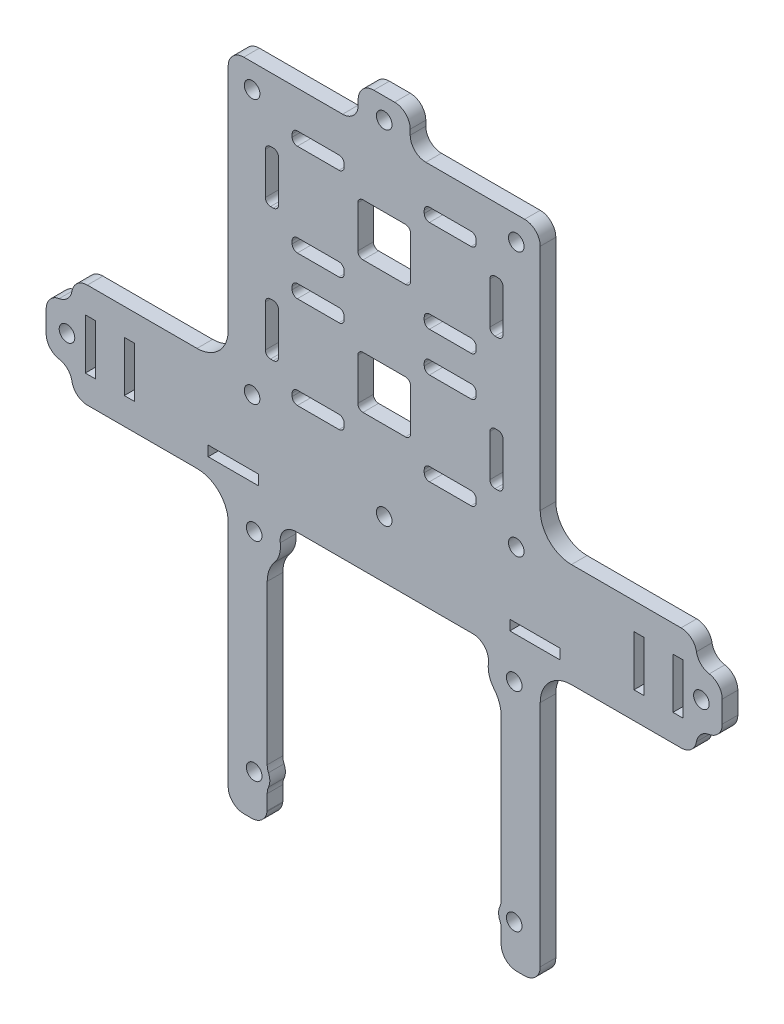
SolidWorks part; units mm, degrees
ref_plane "Спереди" through (0, 0, 0) normal (0, 0, 1) x (1, 0, 0)
ref_plane "Сверху" through (0, 0, 0) normal (0, 1, 0) x (1, 0, 0)
ref_plane "Справа" through (0, 0, 0) normal (1, 0, 0) x (0, 0, -1)
sketch "Model" plane through (0, 0, 0) normal (0, 0, 1) x (1, 0, 0)
  line L0 (5.08, 16.3) -> (5.08, 24.3)
  line L1 (4.08, 25.3) -> (-4.08, 25.3)
  line L2 (-5.08, 24.3) -> (-5.08, 16.3)
  line L3 (-4.08, 15.3) -> (4.08, 15.3)
  line L4 (5.08, 41.7) -> (5.08, 49.7)
  line L5 (4.08, 50.7) -> (-4.08, 50.7)
  line L6 (-5.08, 49.7) -> (-5.08, 41.7)
  line L7 (-4.08, 40.7) -> (4.08, 40.7)
  line L8 (16.7, 55.86) -> (8.7, 55.86)
  line L9 (7.7, 54.86) -> (7.7, 54.32)
  line L10 (8.7, 53.32) -> (16.7, 53.32)
  line L11 (17.7, 54.32) -> (17.7, 54.86)
  line L12 (22.86, 41.7) -> (22.86, 49.7)
  line L13 (21.86, 50.7) -> (21.32, 50.7)
  line L14 (20.32, 49.7) -> (20.32, 41.7)
  line L15 (21.32, 40.7) -> (21.86, 40.7)
  line L16 (22.86, 16.3) -> (22.86, 24.3)
  line L17 (21.86, 25.3) -> (21.32, 25.3)
  line L18 (20.32, 24.3) -> (20.32, 16.3)
  line L19 (21.32, 15.3) -> (21.86, 15.3)
  line L20 (8.7, 10.14) -> (16.7, 10.14)
  line L21 (17.7, 11.14) -> (17.7, 11.68)
  line L22 (16.7, 12.68) -> (8.7, 12.68)
  line L23 (7.7, 11.68) -> (7.7, 11.14)
  line L24 (16.7, 30.46) -> (8.7, 30.46)
  line L25 (7.7, 29.46) -> (7.7, 28.92)
  line L26 (8.7, 27.92) -> (16.7, 27.92)
  line L27 (17.7, 28.92) -> (17.7, 29.46)
  line L28 (-8.7, 30.46) -> (-16.7, 30.46)
  line L29 (-17.7, 29.46) -> (-17.7, 28.92)
  line L30 (-16.7, 27.92) -> (-8.7, 27.92)
  line L31 (-7.7, 28.92) -> (-7.7, 29.46)
  line L32 (-8.7, 38.08) -> (-16.7, 38.08)
  line L33 (-17.7, 37.08) -> (-17.7, 36.54)
  line L34 (-16.7, 35.54) -> (-8.7, 35.54)
  line L35 (-7.7, 36.54) -> (-7.7, 37.08)
  line L36 (-16.7, 10.14) -> (-8.7, 10.14)
  line L37 (-7.7, 11.14) -> (-7.7, 11.68)
  line L38 (-8.7, 12.68) -> (-16.7, 12.68)
  line L39 (-17.7, 11.68) -> (-17.7, 11.14)
  line L40 (-22.86, 24.3) -> (-22.86, 16.3)
  line L41 (-21.86, 15.3) -> (-21.32, 15.3)
  line L42 (-20.32, 16.3) -> (-20.32, 24.3)
  line L43 (-21.32, 25.3) -> (-21.86, 25.3)
  line L44 (-20.32, 41.7) -> (-20.32, 49.7)
  line L45 (-21.32, 50.7) -> (-21.86, 50.7)
  line L46 (-22.86, 49.7) -> (-22.86, 41.7)
  line L47 (-21.86, 40.7) -> (-21.32, 40.7)
  line L48 (36, -10) -> (57.0839, -10)
  line L49 (30, -60) -> (30, -16)
  line L50 (27, -63) -> (25.5, -63)
  line L51 (-25.5, -63) -> (-27, -63)
  line L52 (-30, -60) -> (-30, -16)
  line L53 (-57.0839, -10) -> (-36, -10)
  line L54 (-65, -2.0839) -> (-65, 2.0839)
  line L55 (-36, 10) -> (-57.0839, 10)
  line L56 (-30, 16) -> (-30, 60)
  line L57 (-8, 63) -> (-27, 63)
  line L58 (-5, 66) -> (-5, 67)
  line L59 (2, 70) -> (-2, 70)
  line L60 (5, 66) -> (5, 67)
  line L61 (27, 63) -> (8, 63)
  line L62 (30, 16) -> (30, 60)
  line L63 (57.0839, 10) -> (36, 10)
  line L64 (65, -2.0839) -> (65, 2.0839)
  line L65 (8.7, 35.54) -> (16.7, 35.54)
  line L66 (17.7, 36.54) -> (17.7, 37.08)
  line L67 (16.7, 38.08) -> (8.7, 38.08)
  line L68 (7.7, 37.08) -> (7.7, 36.54)
  line L69 (-16.7, 53.32) -> (-8.7, 53.32)
  line L70 (-7.7, 54.32) -> (-7.7, 54.86)
  line L71 (-8.7, 55.86) -> (-16.7, 55.86)
  line L72 (-17.7, 54.86) -> (-17.7, 54.32)
  line L73 (-24.15, -6.975) -> (-24.15, -5.025)
  line L74 (-24.15, -5.025) -> (-33.85, -5.025)
  line L75 (-33.85, -5.025) -> (-33.85, -6.975)
  line L76 (-33.85, -6.975) -> (-24.15, -6.975)
  line L77 (33.85, -6.975) -> (33.85, -5.025)
  line L78 (33.85, -5.025) -> (24.15, -5.025)
  line L79 (24.15, -5.025) -> (24.15, -6.975)
  line L80 (24.15, -6.975) -> (33.85, -6.975)
  line L81 (49.975, 4.85) -> (48.025, 4.85)
  line L82 (48.025, 4.85) -> (48.025, -4.85)
  line L83 (48.025, -4.85) -> (49.975, -4.85)
  line L84 (49.975, -4.85) -> (49.975, 4.85)
  line L85 (-49.975, 4.85) -> (-48.025, 4.85)
  line L86 (-48.025, 4.85) -> (-48.025, -4.85)
  line L87 (-48.025, -4.85) -> (-49.975, -4.85)
  line L88 (-49.975, -4.85) -> (-49.975, 4.85)
  line L89 (-57.475, 4.85) -> (-55.525, 4.85)
  line L90 (-55.525, 4.85) -> (-55.525, -4.85)
  line L91 (-55.525, -4.85) -> (-57.475, -4.85)
  line L92 (-57.475, -4.85) -> (-57.475, 4.85)
  line L93 (57.475, 4.85) -> (55.525, 4.85)
  line L94 (55.525, 4.85) -> (55.525, -4.85)
  line L95 (55.525, -4.85) -> (57.475, -4.85)
  line L96 (57.475, -4.85) -> (57.475, 4.85)
  line L97 (-22.5, -22.0631) -> (-22.5, -52.6021)
  line L98 (22.5, -21.9821) -> (22.5, -52.6021)
  line L99 (0, -11) -> (-17.0108, -11)
  line L100 (0, -11) -> (17.0627, -11)
  line L101 (-22.5, -57.3979) -> (-22.5, -60.2561)
  line L102 (22.5, -57.3979) -> (22.5, -60.2561)
  circle A0 centre (-25.4, 58.4) radius 1.5
  circle A1 centre (25.4, 7.6) radius 1.5
  circle A2 centre (-25.4, 7.6) radius 1.5
  circle A3 centre (25.4, 58.4) radius 1.5
  circle A4 centre (0, 0) radius 1.5
  circle A5 centre (0, 66) radius 1.5
  circle A6 centre (61, 0) radius 1.5
  circle A7 centre (-61, 0) radius 1.5
  arc A8 (57.0839, -10) -> (60.042, -7.5) centre (57.0839, -7) ccw
  arc A9 (27, -63) -> (30, -60) centre (27, -60) ccw
  arc A10 (-30, -60) -> (-27, -63) centre (-27, -60) ccw
  arc A11 (-60.042, -7.5) -> (-57.0839, -10) centre (-57.0839, -7) ccw
  arc A12 (-60.042, -7.5) -> (-62.5, -5.042) centre (-63, -8) ccw
  arc A13 (-65, -2.0839) -> (-62.5, -5.042) centre (-62, -2.0839) ccw
  arc A14 (-62.5, 5.042) -> (-65, 2.0839) centre (-62, 2.0839) ccw
  arc A15 (-62.5, 5.042) -> (-60.042, 7.5) centre (-63, 8) ccw
  arc A16 (-57.0839, 10) -> (-60.042, 7.5) centre (-57.0839, 7) ccw
  arc A17 (-27, 63) -> (-30, 60) centre (-27, 60) ccw
  arc A18 (-8, 63) -> (-5, 66) centre (-8, 66) ccw
  arc A19 (-2, 70) -> (-5, 67) centre (-2, 67) ccw
  arc A20 (5, 67) -> (2, 70) centre (2, 67) ccw
  arc A21 (5, 66) -> (8, 63) centre (8, 66) ccw
  arc A22 (30, 60) -> (27, 63) centre (27, 60) ccw
  arc A23 (60.042, 7.5) -> (57.0839, 10) centre (57.0839, 7) ccw
  arc A24 (60.042, 7.5) -> (62.5, 5.042) centre (63, 8) ccw
  arc A25 (65, 2.0839) -> (62.5, 5.042) centre (62, 2.0839) ccw
  arc A26 (62.5, -5.042) -> (65, -2.0839) centre (62, -2.0839) ccw
  arc A27 (62.5, -5.042) -> (60.042, -7.5) centre (63, -8) ccw
  arc A28 (-36, 10) -> (-30, 16) centre (-36, 16) ccw
  arc A29 (-30, -16) -> (-36, -10) centre (-36, -16) ccw
  arc A30 (36, -10) -> (30, -16) centre (36, -16) ccw
  arc A31 (30, 16) -> (36, 10) centre (36, 16) ccw
  arc A32 (-16.7, 55.86) -> (-17.7, 54.86) centre (-16.7, 54.86) ccw
  arc A33 (-17.7, 54.32) -> (-16.7, 53.32) centre (-16.7, 54.32) ccw
  arc A34 (-8.7, 53.32) -> (-7.7, 54.32) centre (-8.7, 54.32) ccw
  arc A35 (-7.7, 54.86) -> (-8.7, 55.86) centre (-8.7, 54.86) ccw
  arc A36 (-20.32, 49.7) -> (-21.32, 50.7) centre (-21.32, 49.7) ccw
  arc A37 (-21.86, 50.7) -> (-22.86, 49.7) centre (-21.86, 49.7) ccw
  arc A38 (-21.32, 40.7) -> (-20.32, 41.7) centre (-21.32, 41.7) ccw
  arc A39 (-22.86, 41.7) -> (-21.86, 40.7) centre (-21.86, 41.7) ccw
  arc A40 (-4.08, 50.7) -> (-5.08, 49.7) centre (-4.08, 49.7) ccw
  arc A41 (-5.08, 41.7) -> (-4.08, 40.7) centre (-4.08, 41.7) ccw
  arc A42 (4.08, 40.7) -> (5.08, 41.7) centre (4.08, 41.7) ccw
  arc A43 (5.08, 49.7) -> (4.08, 50.7) centre (4.08, 49.7) ccw
  arc A44 (7.7, 54.32) -> (8.7, 53.32) centre (8.7, 54.32) ccw
  arc A45 (8.7, 55.86) -> (7.7, 54.86) centre (8.7, 54.86) ccw
  arc A46 (17.7, 54.86) -> (16.7, 55.86) centre (16.7, 54.86) ccw
  arc A47 (16.7, 53.32) -> (17.7, 54.32) centre (16.7, 54.32) ccw
  arc A48 (21.32, 50.7) -> (20.32, 49.7) centre (21.32, 49.7) ccw
  arc A49 (22.86, 49.7) -> (21.86, 50.7) centre (21.86, 49.7) ccw
  arc A50 (21.86, 40.7) -> (22.86, 41.7) centre (21.86, 41.7) ccw
  arc A51 (20.32, 41.7) -> (21.32, 40.7) centre (21.32, 41.7) ccw
  arc A52 (-4.08, 25.3) -> (-5.08, 24.3) centre (-4.08, 24.3) ccw
  arc A53 (5.08, 24.3) -> (4.08, 25.3) centre (4.08, 24.3) ccw
  arc A54 (4.08, 15.3) -> (5.08, 16.3) centre (4.08, 16.3) ccw
  arc A55 (-5.08, 16.3) -> (-4.08, 15.3) centre (-4.08, 16.3) ccw
  arc A56 (-16.7, 12.68) -> (-17.7, 11.68) centre (-16.7, 11.68) ccw
  arc A57 (-8.7, 10.14) -> (-7.7, 11.14) centre (-8.7, 11.14) ccw
  arc A58 (-7.7, 11.68) -> (-8.7, 12.68) centre (-8.7, 11.68) ccw
  arc A59 (-17.7, 11.14) -> (-16.7, 10.14) centre (-16.7, 11.14) ccw
  arc A60 (-22.86, 16.3) -> (-21.86, 15.3) centre (-21.86, 16.3) ccw
  arc A61 (-21.32, 15.3) -> (-20.32, 16.3) centre (-21.32, 16.3) ccw
  arc A62 (-21.86, 25.3) -> (-22.86, 24.3) centre (-21.86, 24.3) ccw
  arc A63 (-20.32, 24.3) -> (-21.32, 25.3) centre (-21.32, 24.3) ccw
  arc A64 (-17.7, 28.92) -> (-16.7, 27.92) centre (-16.7, 28.92) ccw
  arc A65 (-16.7, 30.46) -> (-17.7, 29.46) centre (-16.7, 29.46) ccw
  arc A66 (-7.7, 29.46) -> (-8.7, 30.46) centre (-8.7, 29.46) ccw
  arc A67 (-8.7, 27.92) -> (-7.7, 28.92) centre (-8.7, 28.92) ccw
  arc A68 (-17.7, 36.54) -> (-16.7, 35.54) centre (-16.7, 36.54) ccw
  arc A69 (-16.7, 38.08) -> (-17.7, 37.08) centre (-16.7, 37.08) ccw
  arc A70 (-7.7, 37.08) -> (-8.7, 38.08) centre (-8.7, 37.08) ccw
  arc A71 (-8.7, 35.54) -> (-7.7, 36.54) centre (-8.7, 36.54) ccw
  arc A72 (7.7, 36.54) -> (8.7, 35.54) centre (8.7, 36.54) ccw
  arc A73 (8.7, 38.08) -> (7.7, 37.08) centre (8.7, 37.08) ccw
  arc A74 (16.7, 35.54) -> (17.7, 36.54) centre (16.7, 36.54) ccw
  arc A75 (17.7, 37.08) -> (16.7, 38.08) centre (16.7, 37.08) ccw
  arc A76 (8.7, 30.46) -> (7.7, 29.46) centre (8.7, 29.46) ccw
  arc A77 (16.7, 27.92) -> (17.7, 28.92) centre (16.7, 28.92) ccw
  arc A78 (17.7, 29.46) -> (16.7, 30.46) centre (16.7, 29.46) ccw
  arc A79 (7.7, 28.92) -> (8.7, 27.92) centre (8.7, 28.92) ccw
  arc A80 (8.7, 12.68) -> (7.7, 11.68) centre (8.7, 11.68) ccw
  arc A81 (16.7, 10.14) -> (17.7, 11.14) centre (16.7, 11.14) ccw
  arc A82 (17.7, 11.68) -> (16.7, 12.68) centre (16.7, 11.68) ccw
  arc A83 (20.32, 16.3) -> (21.32, 15.3) centre (21.32, 16.3) ccw
  arc A84 (21.86, 15.3) -> (22.86, 16.3) centre (21.86, 16.3) ccw
  arc A85 (22.86, 24.3) -> (21.86, 25.3) centre (21.86, 24.3) ccw
  arc A86 (21.32, 25.3) -> (20.32, 24.3) centre (21.32, 24.3) ccw
  arc A87 (7.7, 11.14) -> (8.7, 10.14) centre (8.7, 11.14) ccw
  circle A88 centre (-25, -15) radius 1.5
  circle A89 centre (25, -15) radius 1.5
  circle A90 centre (-25, -55) radius 1.5
  circle A91 centre (25, -55) radius 1.5
  arc A92 (-25.5, -63) -> (-22.5316, -60.4343) centre (-25.5, -60) ccw
  arc A93 (22.5316, -60.4343) -> (25.5, -63) centre (25.5, -60) ccw
  arc A94 (20.0392, -14.375) -> (21.1364, -18.1737) centre (25, -15) ccw
  arc A95 (-21.1147, -18.2285) -> (-19.9875, -14.3726) centre (-25, -15) ccw
  arc A96 (-30.0442, -15.2734) -> (-30.0108, -15.6407) centre (-25, -15) ccw
  arc A97 (-17.0108, -11) -> (-19.9875, -14.3726) centre (-17.0108, -14) ccw
  arc A98 (20.0392, -14.375) -> (17.0627, -11) centre (17.0627, -14) ccw
  arc A99 (22.5, -21.9821) -> (21.1364, -18.1737) centre (16.5, -21.9821) ccw
  arc A100 (-21.1147, -18.2285) -> (-22.5, -22.0631) centre (-16.5, -22.0631) ccw
  arc A101 (-22.5, -60.2561) -> (-22.5316, -60.4343) centre (-19.5632, -60.8687) ccw
  arc A102 (22.5316, -60.4343) -> (22.5, -60.2561) centre (19.5632, -60.8687) ccw
  arc A103 (22.5, -57.3979) -> (22.25, -56.199) centre (19.5, -57.3979) ccw
  arc A104 (-22.25, -56.199) -> (-22.25, -53.801) centre (-25, -55) ccw
  arc A105 (22.25, -53.801) -> (22.25, -56.199) centre (25, -55) ccw
  arc A106 (22.5, -52.6021) -> (22.25, -53.801) centre (19.5, -52.6021) cw
  arc A107 (-22.5, -52.6021) -> (-22.25, -53.801) centre (-19.5, -52.6021) ccw
  arc A108 (-22.25, -56.199) -> (-22.5, -57.3979) centre (-19.5, -57.3979) ccw
  dimension "D1" = 3
  dimension "D2" = 3
  dimension "D3" = 3
extrude "Бобышка-Вытянуть1" add sketch "Model" against normal blind 3 contours A108 A104 A107 L97 A100 A95 A97 L99 L100 A98 A94 A99 L98 A106 A105 A103 L102 A102 A93 L50 A9 L49 A30 L48 A8 A27 A26 L64 A25 A24 A23 L63 A31 L62 A22 L61 A21 L60 A20 L59 A19 L58 A18 L57 A17 L56 A28 L55 A16 A15 A14
